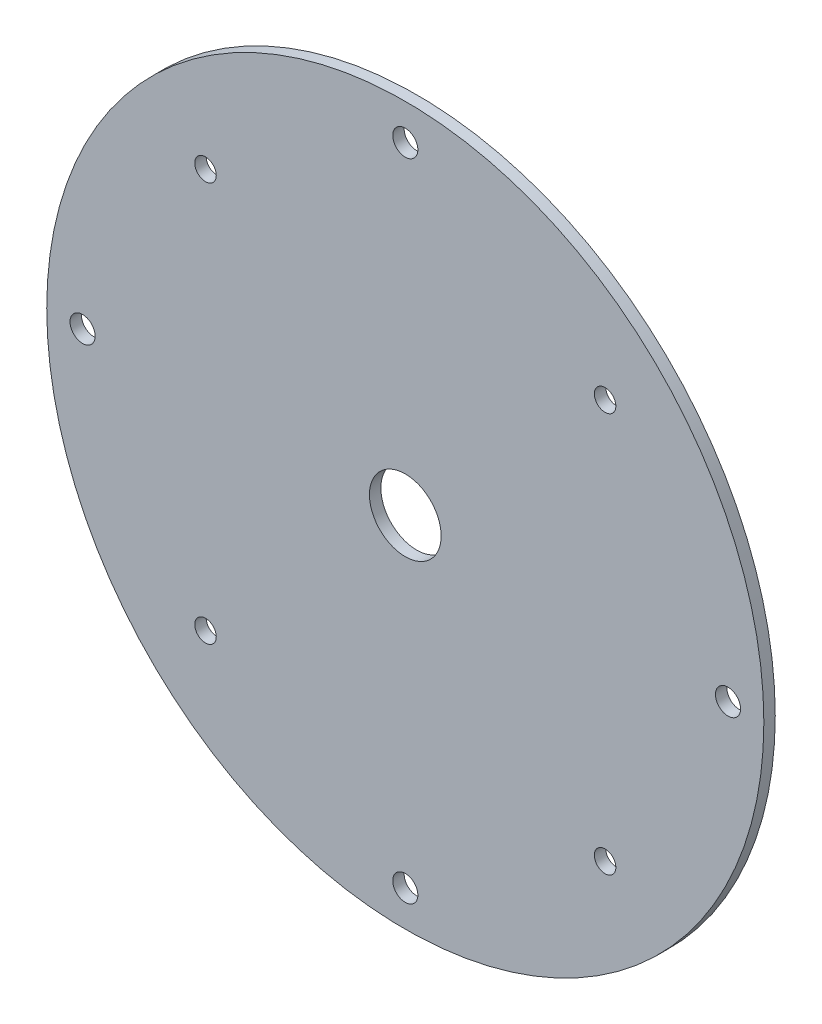
SolidWorks part; units mm, degrees
material "6061 Alloy"
ref_plane "Front Plane" through (0, 0, 0) normal (0, 0, 1) x (1, 0, 0)
ref_plane "Top Plane" through (0, 0, 0) normal (0, 1, 0) x (1, 0, 0)
ref_plane "Right Plane" through (0, 0, 0) normal (1, 0, 0) x (0, 0, -1)
sketch "Sketch1" plane through (0, 0, 0) normal (0, 0, 1) x (1, 0, 0)
  circle A0 centre (0, 0) radius 50
  circle A1 centre (0, 0) radius 5
  dimension "D1" = 100
  dimension "D2" = 10
extrude "Boss-Extrude1" add sketch "Sketch1" along normal blind 1.59
sketch "Sketch2" plane through (0, 0, 1.59) normal (0, 0, 1) x (1, 0, 0)
  circle A0 centre (0, 0) radius 45 construction
  circle A1 centre (0, 45) radius 1.75
  circle A2 centre (45, 0) radius 1.75
  circle A3 centre (0, -45) radius 1.75
  circle A4 centre (-45, 0) radius 1.75
  point P14 (0, 0)
  dimension "D1" = 90
  dimension "D2" = 3.5
  dimension "D3" = 4
extrude "Cut-Extrude1" cut sketch "Sketch2" against normal blind 1.59
sketch "Sketch3" plane through (0, 0, 1.59) normal (0, 0, 1) x (1, 0, 0)
  circle A0 centre (0, 0) radius 39.4 construction
  circle A1 centre (-27.86, 27.86) radius 1.5
  circle A2 centre (27.86, 27.86) radius 1.5
  circle A3 centre (27.86, -27.86) radius 1.5
  circle A4 centre (-27.86, -27.86) radius 1.5
  point P14 (0, 0)
  dimension "D1" = 78.8
  dimension "D2" = 3
  dimension "D3" = 27.86
  dimension "D4" = 4
extrude "Cut-Extrude2" cut sketch "Sketch3" against normal blind 10
